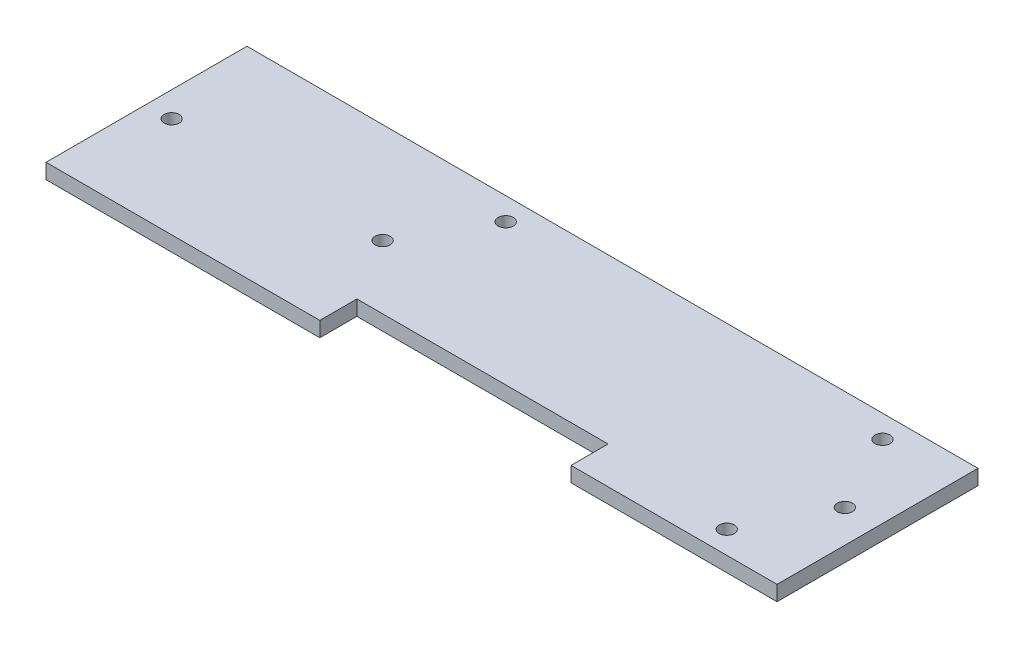
SolidWorks part; units mm, degrees
ref_plane "Front Plane" through (0, 0, 0) normal (0, 0, 1) x (1, 0, 0)
ref_plane "Top Plane" through (0, 0, 0) normal (0, 1, 0) x (1, 0, 0)
ref_plane "Right Plane" through (0, 0, 0) normal (1, 0, 0) x (0, 0, -1)
sketch "Sketch1" plane through (0, 0, 0) normal (0, 1, 0) x (1, 0, 0)
  line L0 (93.5, -20) -> (145.5081, -20) construction
  line L1 (0, 0) -> (145.5081, 0)
  line L2 (0, 0) -> (0, -40)
  line L3 (0, -40) -> (145.5081, -40)
  line L4 (145.5081, 0) -> (145.5081, -40)
  line L5 (56, -4.5) -> (131, -4.5) construction
  line L6 (56, -4.5) -> (56, -35.5) construction
  line L7 (56, -35.5) -> (131, -35.5) construction
  line L8 (131, -4.5) -> (131, -35.5) construction
  line L9 (56, -4.5) -> (131, -35.5) construction
  line L10 (56, -35.5) -> (131, -4.5) construction
  line L11 (47, -20) -> (5, -20) construction
  line L13 (54.5, -61.7589) -> (104.5, -61.7589)
  line L14 (54.5, -61.7589) -> (54.5, -32.6202)
  line L15 (54.5, -32.6202) -> (104.5, -32.6202)
  line L16 (104.5, -61.7589) -> (104.5, -32.6202)
  circle A0 centre (5, -20) radius 1.5
  circle A1 centre (47, -20) radius 1.5
  circle A2 centre (56, -35.5) radius 1.5
  circle A3 centre (131, -35.5) radius 1.5
  circle A4 centre (131, -4.5) radius 1.5
  circle A5 centre (56, -4.5) radius 1.5
  circle A6 centre (139, -20) radius 1.5
  point P5 (93.5, -20)
  point P26 (138.2593, -20)
  dimension "D4" = 3
  dimension "D1" = 75
  dimension "D2" = 31
  dimension "D3" = 40
  dimension "D5" = 9
  dimension "D6" = 42
  dimension "D7" = 5
  dimension "D8" = 50
  dimension "D9" = 8
extrude "Boss-Extrude1" add sketch "Sketch1" along normal blind 3 contours L16 L3 L4 L1 L2 L14 L15 A6 A5 A4 A3 A1 A0
